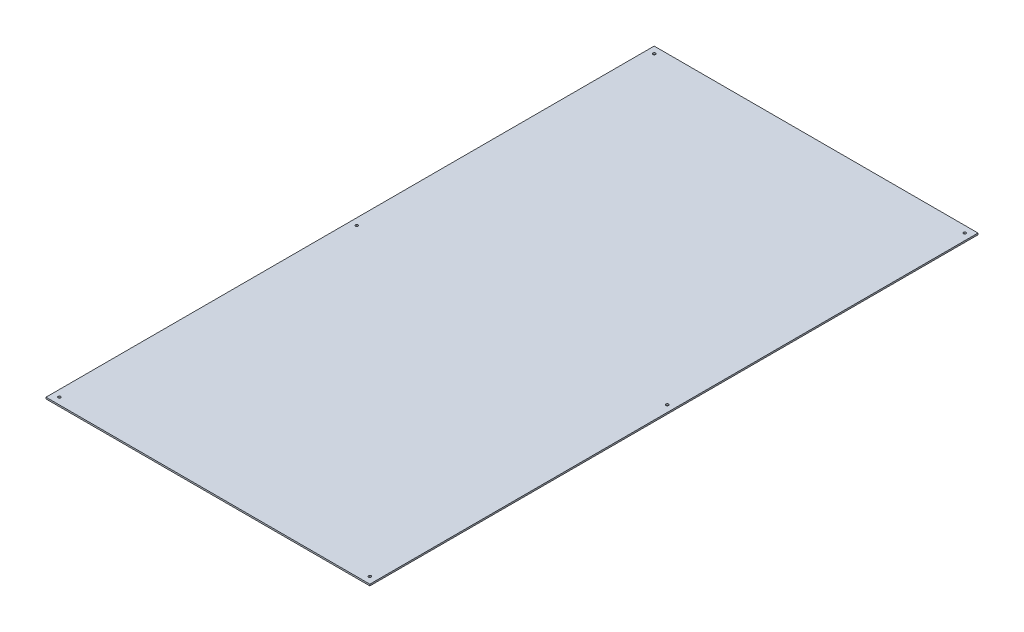
SolidWorks part; units mm, degrees
ref_plane "Front Plane" through (0, 0, 0) normal (0, 0, 1) x (1, 0, 0)
ref_plane "Top Plane" through (0, 0, 0) normal (0, 1, 0) x (1, 0, 0)
ref_plane "Right Plane" through (0, 0, 0) normal (1, 0, 0) x (0, 0, -1)
sketch "Sketch1" plane through (0, 0, 0) normal (0, 1, 0) x (1, 0, 0)
  line L0 (279, 534.5) -> (279, -534.5) construction
  line L1 (291, 546.5) -> (-291, 546.5)
  line L2 (291, 546.5) -> (291, -546.5)
  line L3 (291, -546.5) -> (-291, -546.5)
  line L4 (-291, 546.5) -> (-291, -546.5)
  line L5 (291, 546.5) -> (-291, -546.5) construction
  line L6 (291, -546.5) -> (-291, 546.5) construction
  line L7 (279, -534.5) -> (-279, -534.5) construction
  line L8 (-279, 534.5) -> (-279, -534.5) construction
  line L9 (279, 534.5) -> (-279, 534.5) construction
  circle A0 centre (279, 534.5) radius 2.3813
  circle A1 centre (-279, 534.5) radius 2.3813
  circle A2 centre (-279, 0) radius 2.3813
  circle A3 centre (279, 0) radius 2.3813
  circle A4 centre (-279, -534.5) radius 2.3813
  circle A5 centre (279, -534.5) radius 2.3813
  point P0 (0, 0)
  dimension "D4" = 4.7625
  dimension "D1" = 1093
  dimension "D2" = 582
  dimension "D3" = 12
extrude "Boss-Extrude1" add sketch "Sketch1" along normal blind 2.8
